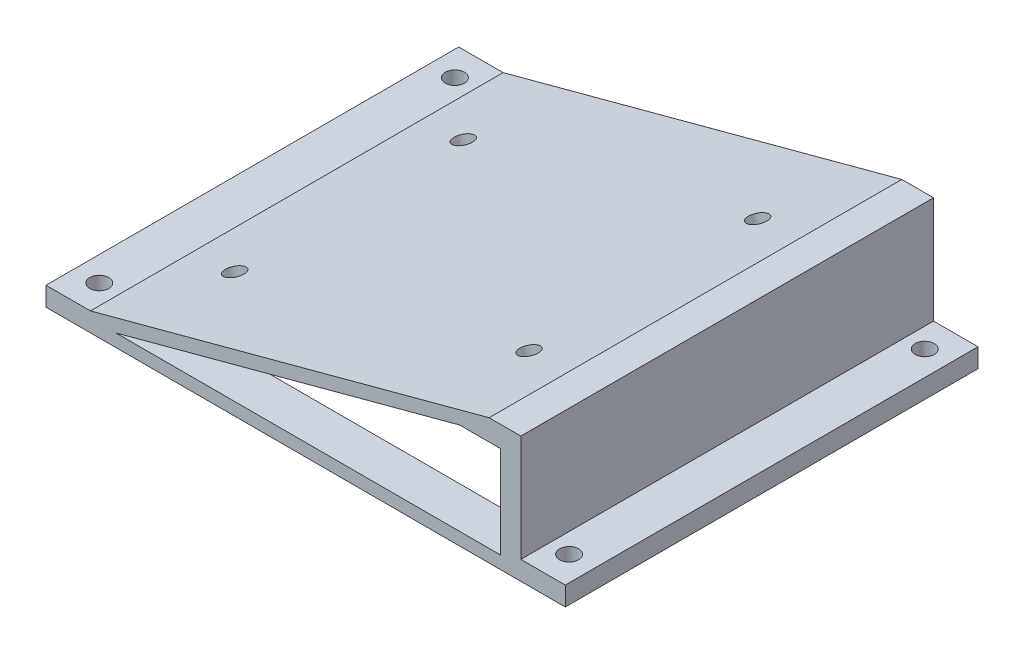
SolidWorks part; units mm, degrees
ref_plane "前视基准面" through (0, 0, 0) normal (0, 0, 1) x (1, 0, 0)
ref_plane "上视基准面" through (0, 0, 0) normal (0, 1, 0) x (1, 0, 0)
ref_plane "右视基准面" through (0, 0, 0) normal (1, 0, 0) x (0, 0, -1)
sketch "草图1" plane through (0, 0, 0) normal (0, 0, 1) x (1, 0, 0)
  line L34 (0, 0) -> (0, 3)
  line L35 (0, 3) -> (7, 3)
  line L36 (7, 3) -> (69.7852, 19.8232)
  line L37 (69.7852, 19.8232) -> (74.7852, 19.8232)
  line L38 (74.7852, 19.8232) -> (74.7852, 3)
  line L39 (74.7852, 3) -> (81.7852, 3)
  line L40 (81.7852, 3) -> (81.7852, 0)
  line L42 (0, 0) -> (81.7852, 0)
  dimension "D5" = 3
  dimension "D1" = 3
  dimension "D2" = 65
  dimension "D3" = 165
  dimension "D4" = 5
  dimension "D6" = 7
  dimension "D7" = 7
extrude "凸台-拉伸4" add sketch "草图1" along normal blind 65
sketch "草图9" plane through (0, 0, 65) normal (0, 0, 1) x (1, 0, 0)
  line L0 (65.1101, 16.5) -> (10.9954, 2)
  line L1 (65.1101, 16.5) -> (71.6101, 16.5)
  line L2 (69.7852, 19.8232) -> (7, 3) construction
  line L6 (71.6101, 2) -> (10.9954, 2)
  line L7 (0, 0) -> (81.7852, 0) construction
  line L9 (71.6101, 16.5) -> (71.6101, 2)
  dimension "D1" = 2
  dimension "D2" = 2
  dimension "D3" = 14.5
  dimension "D4" = 6.5
extrude "切除-拉伸2" cut sketch "草图9" against normal blind 24.5
sketch "草图10" plane through (0, 0, 0) normal (0, 0, -1) x (-1, 0, 0)
  line L1 (-71.6101, 2) -> (-10.9954, 2)
  line L2 (-10.9954, 2) -> (-65.1101, 16.5)
  line L3 (-65.1101, 16.5) -> (-71.6101, 16.5)
  line L4 (-69.7852, 19.8232) -> (-7, 3) construction
  line L5 (0, 0) -> (-81.7852, 0) construction
  line L7 (-71.6101, 16.5) -> (-71.6101, 2)
  dimension "D1" = 2
  dimension "D2" = 2
  dimension "D3" = 14.5
  dimension "D4" = 6.5
extrude "切除-拉伸3" cut sketch "草图10" against normal blind 24.5
sketch "草图11" plane through (0, 0, 0) normal (0, -1, 0) x (1, 0, 0)
  line L0 (0, 32.5) -> (81.7852, 32.5) construction
  line L1 (0, 65) -> (0, 0) construction
  line L2 (81.7852, 65) -> (81.7852, 0) construction
  line L3 (40.8926, 65) -> (40.8926, 0) construction
  line L4 (0, 0) -> (81.7852, 0) construction
  line L6 (3.8926, 60.5) -> (77.8926, 60.5) construction
  line L7 (3.8926, 60.5) -> (3.8926, 4.5) construction
  line L8 (3.8926, 4.5) -> (77.8926, 4.5) construction
  line L9 (77.8926, 60.5) -> (77.8926, 4.5) construction
  line L10 (3.8926, 60.5) -> (77.8926, 4.5) construction
  line L11 (3.8926, 4.5) -> (77.8926, 60.5) construction
  line L21 (71.6052, 58.5) -> (71.6052, 40.5)
  line L22 (71.6052, 40.5) -> (11, 40.5)
  line L24 (11, 40.5) -> (11, 58.5)
  line L25 (11, 58.5) -> (71.6052, 58.5)
  line L26 (11, 24.5) -> (11, 6.5)
  line L27 (71.6052, 24.5) -> (11, 24.5)
  line L28 (71.6052, 6.5) -> (71.6052, 24.5)
  line L29 (11, 6.5) -> (71.6052, 6.5)
  circle A0 centre (3.8926, 60.5) radius 1.5
  circle A1 centre (77.8926, 60.5) radius 1.5
  circle A2 centre (77.8926, 4.5) radius 1.5
  circle A3 centre (3.8926, 4.5) radius 1.5
  point P6 (40.8926, 32.5)
  point P11 (40.8926, 32.5)
  dimension "D3" = 3
  dimension "D1" = 56
  dimension "D2" = 74
  dimension "D4" = 11
  dimension "D5" = 10.18
  dimension "D6" = 8
  dimension "D7" = 18
extrude "切除-拉伸5" cut sketch "草图11" against normal up to next
sketch "草图8" plane through (-0.2811, 1.049, 0) normal (-0.2588, 0.9659, 0) x (0.9659, 0.2588, 0)
  line L0 (7.5379, -32.5) -> (72.5379, -32.5) construction
  line L1 (7.5379, -65) -> (7.5379, 0) construction
  line L2 (72.5379, -65) -> (72.5379, 0) construction
  line L3 (40.0379, 0) -> (40.0379, -65) construction
  line L4 (72.5379, -65) -> (7.5379, -65) construction
  line L6 (16.0379, -14.5) -> (64.0379, -14.5) construction
  line L7 (16.0379, -14.5) -> (16.0379, -50.5) construction
  line L8 (16.0379, -50.5) -> (64.0379, -50.5) construction
  line L9 (64.0379, -14.5) -> (64.0379, -50.5) construction
  line L10 (16.0379, -14.5) -> (64.0379, -50.5) construction
  line L11 (16.0379, -50.5) -> (64.0379, -14.5) construction
  circle A0 centre (16.0379, -14.5) radius 1.5
  circle A1 centre (64.0379, -14.5) radius 1.5
  circle A2 centre (64.0379, -50.5) radius 1.5
  circle A3 centre (16.0379, -50.5) radius 1.5
  point P6 (40.0379, -32.5)
  point P11 (40.0379, -32.5)
  point P31 (40.0379, -22.5)
  dimension "D3" = 3
  dimension "D1" = 36
  dimension "D2" = 48
extrude "切除-拉伸4" cut sketch "草图8" against normal up to next
